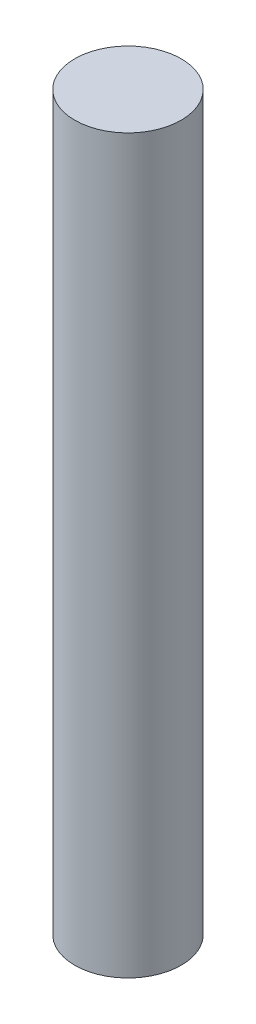
SolidWorks part; units mm, degrees
ref_plane "Front Plane" through (0, 0, 0) normal (0, 0, 1) x (1, 0, 0)
ref_plane "Top Plane" through (0, 0, 0) normal (0, 1, 0) x (1, 0, 0)
ref_plane "Right Plane" through (0, 0, 0) normal (1, 0, 0) x (0, 0, -1)
sketch "Sketch1" plane through (0, 0, 0) normal (0, 1, 0) x (1, 0, 0)
  circle A0 centre (0, 0) radius 4
  dimension "D1" = 8
extrude "Boss-Extrude1" add sketch "Sketch1" along normal blind 55
